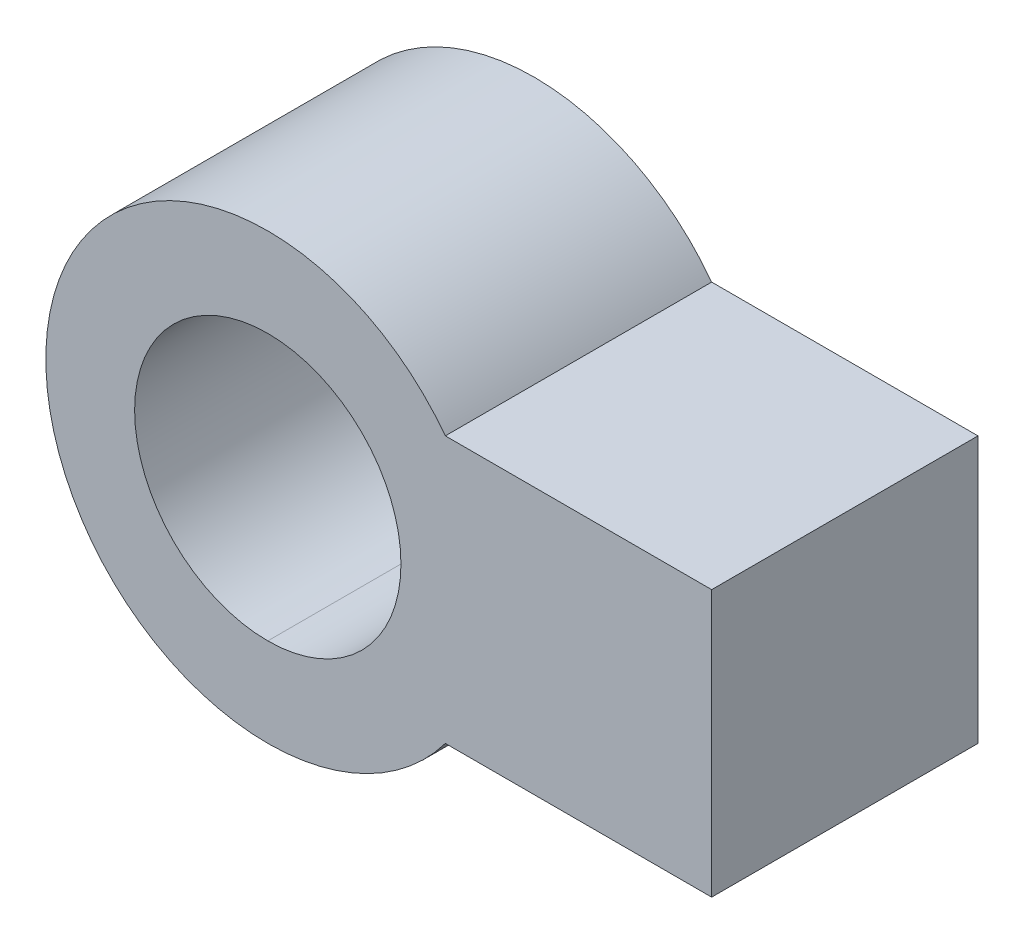
SolidWorks part; units mm, degrees
ref_plane "Front Plane" through (0, 0, 0) normal (0, 0, 1) x (1, 0, 0)
ref_plane "Top Plane" through (0, 0, 0) normal (0, 1, 0) x (1, 0, 0)
ref_plane "Right Plane" through (0, 0, 0) normal (1, 0, 0) x (0, 0, -1)
sketch "Sketch1" plane through (0, 0, 0) normal (0, 0, 1) x (1, 0, 0)
  line L0 (0, 0) -> (15, 0) construction
  line L5 (0, -3) -> (10, -3)
  line L6 (0, -3) -> (0, 3)
  line L7 (0, 3) -> (10, 3)
  line L8 (10, -3) -> (10, 3)
  circle A0 centre (0, 0) radius 5
  circle A2 centre (0, 0) radius 3
  dimension "D2" = 10
  dimension "D3" = 10
  dimension "D4" = 6
  dimension "D5" = 6
  dimension "D1" = 15
extrude "Boss-Extrude1" add sketch "Sketch1" along normal blind 6
